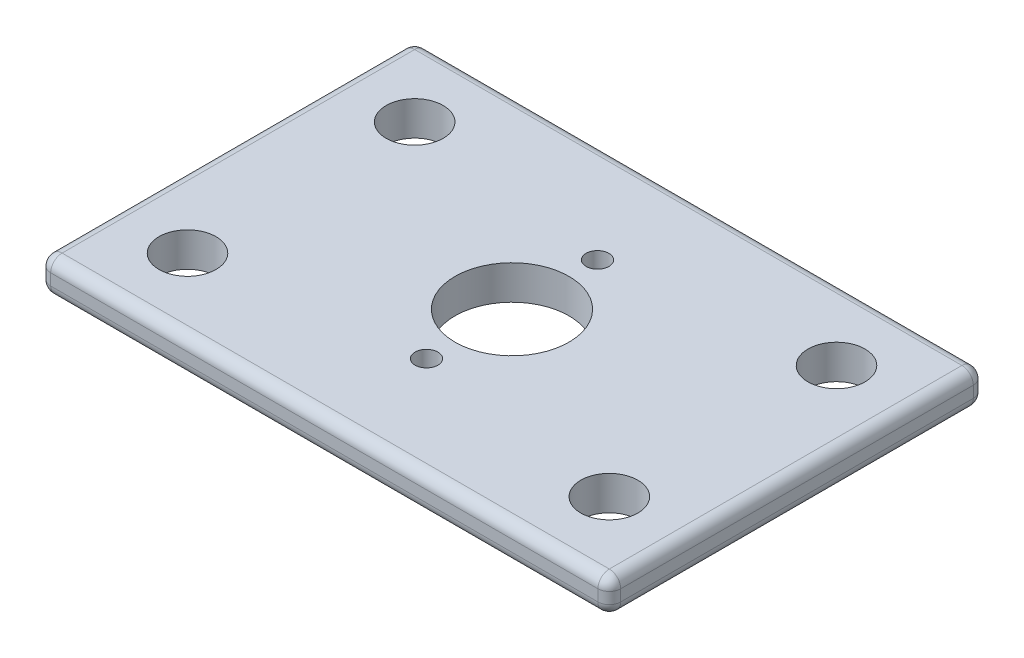
SolidWorks part; units mm, degrees
ref_plane "Front Plane" through (0, 0, 0) normal (0, 0, 1) x (1, 0, 0)
ref_plane "Top Plane" through (0, 0, 0) normal (0, 1, 0) x (1, 0, 0)
ref_plane "Right Plane" through (0, 0, 0) normal (1, 0, 0) x (0, 0, -1)
sketch "Sketch1" plane through (0, 0, 0) normal (0, 1, 0) x (1, 0, 0)
  line L1 (0, 0) -> (50, 0)
  line L2 (0, 0) -> (0, 32.9268)
  line L3 (0, 32.9268) -> (50, 32.9268)
  line L4 (50, 0) -> (50, 32.9268)
  dimension "D1" = 50
extrude "Boss-Extrude1" add sketch "Sketch1" along normal blind 3
sketch "Sketch2" plane through (0, 3, 0) normal (0, 1, 0) x (1, 0, 0)
  line L0 (25, 0) -> (25, 32.9268) construction
  line L1 (0, 0) -> (50, 0) construction
  line L2 (50, 32.9268) -> (0, 32.9268) construction
  line L3 (25, 16.4634) -> (25, 8.9634) construction
  line L4 (25, 8.9634) -> (25, 23.9634) construction
  circle A0 centre (25, 8.9634) radius 1
  circle A1 centre (25, 23.9634) radius 1
  circle A2 centre (25, 16.4634) radius 5
  dimension "D1" = 2
  dimension "D2" = 2
  dimension "D3" = 10
  dimension "D4" = 7.5
  dimension "D5" = 7.5
extrude "Cut-Extrude1" cut sketch "Sketch2" against normal up to next contours A0 | A2 | A1
sketch "Sketch3" plane through (0, 3, 0) normal (0, 1, 0) x (1, 0, 0)
  line L0 (50, 16.4634) -> (43.5, 16.4634) construction
  line L1 (50, 0) -> (50, 32.9268) construction
  line L2 (43.5, 16.4634) -> (43.5, 6.5) construction
  line L3 (25, 9.9634) -> (25, 11.4634) construction
  line L4 (0, 0) -> (50, 0) construction
  circle A0 centre (43.5, 6.5) radius 2.5
  circle A1 centre (43.5, 26.4268) radius 2.5
  circle A2 centre (25, 8.9634) radius 1 construction
  circle A3 centre (25, 16.4634) radius 5 construction
  circle A4 centre (6.5, 26.4268) radius 2.5
  circle A5 centre (6.5, 6.5) radius 2.5
  dimension "D4" = 5
  dimension "D1" = 6.5
  dimension "D2" = 25
  dimension "D3" = 6.5
extrude "Cut-Extrude2" cut sketch "Sketch3" against normal up to next
fillet "Fillet1" radius 1 12 edges at (0, 1.5, 0) (25, 0, 0) (50, 0, -16.4634) (25, 0, -32.9268) (0, 0, -16.4634) (0, 1.5, -32.9268) (50, 1.5, -32.9268) (50, 1.5, 0) (0, 3, -16.4634) (25, 3, -32.9268) (25, 3, 0) (50, 3, -16.4634)
